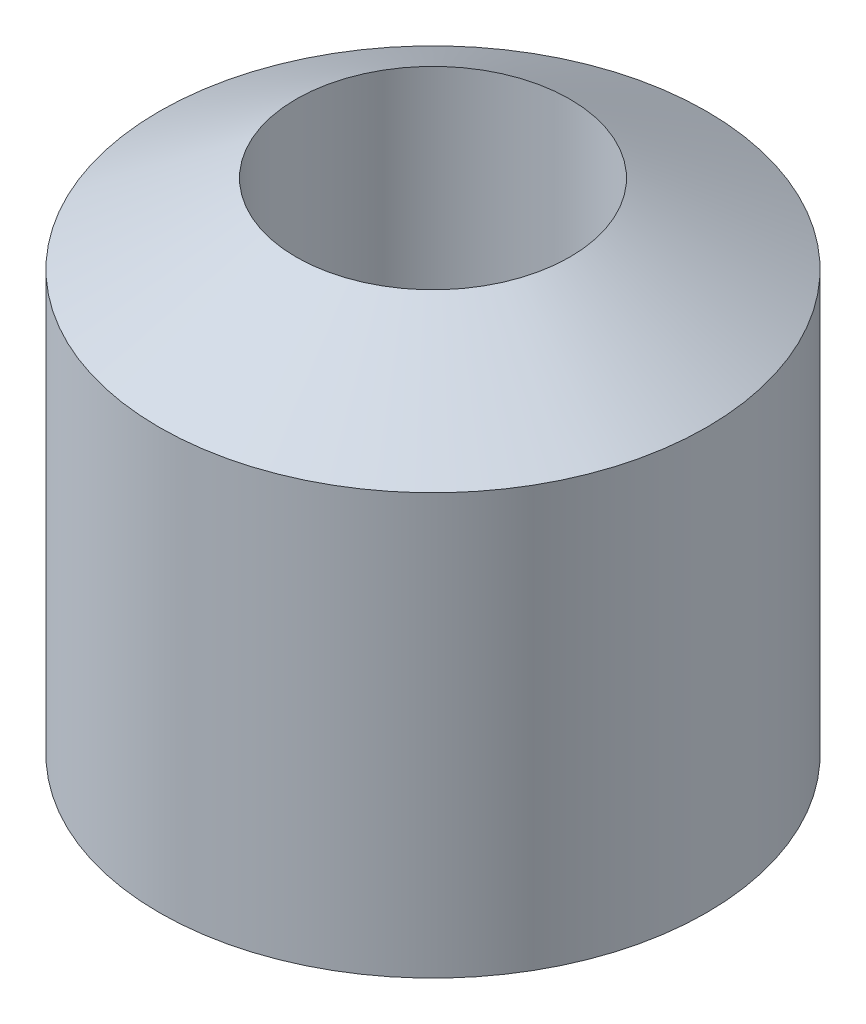
SolidWorks part; units mm, degrees
ref_plane "Front Plane" through (0, 0, 0) normal (0, 0, 1) x (1, 0, 0)
ref_plane "Top Plane" through (0, 0, 0) normal (0, 1, 0) x (1, 0, 0)
ref_plane "Right Plane" through (0, 0, 0) normal (1, 0, 0) x (0, 0, -1)
sketch "Sketch1" plane through (0, 0, 0) normal (0, 0, 1) x (1, 0, 0)
  line L0 (0, 45.9146) -> (0, -39.6225) construction
  line L1 (-37.7091, 0) -> (48.2168, 0) construction
  line L2 (14, 29.5829) -> (28, 21.5)
  line L3 (14, -29.5829) -> (28, -21.5)
  line L4 (28, 21.5) -> (28, -21.5)
  line L5 (14, 29.5829) -> (14, -29.5829)
  dimension "D1" = 60
  dimension "D2" = 14
  dimension "D3" = 28
  dimension "D4" = 43
revolve "Revolve1" add sketch "Sketch1" angle 360 about L0
